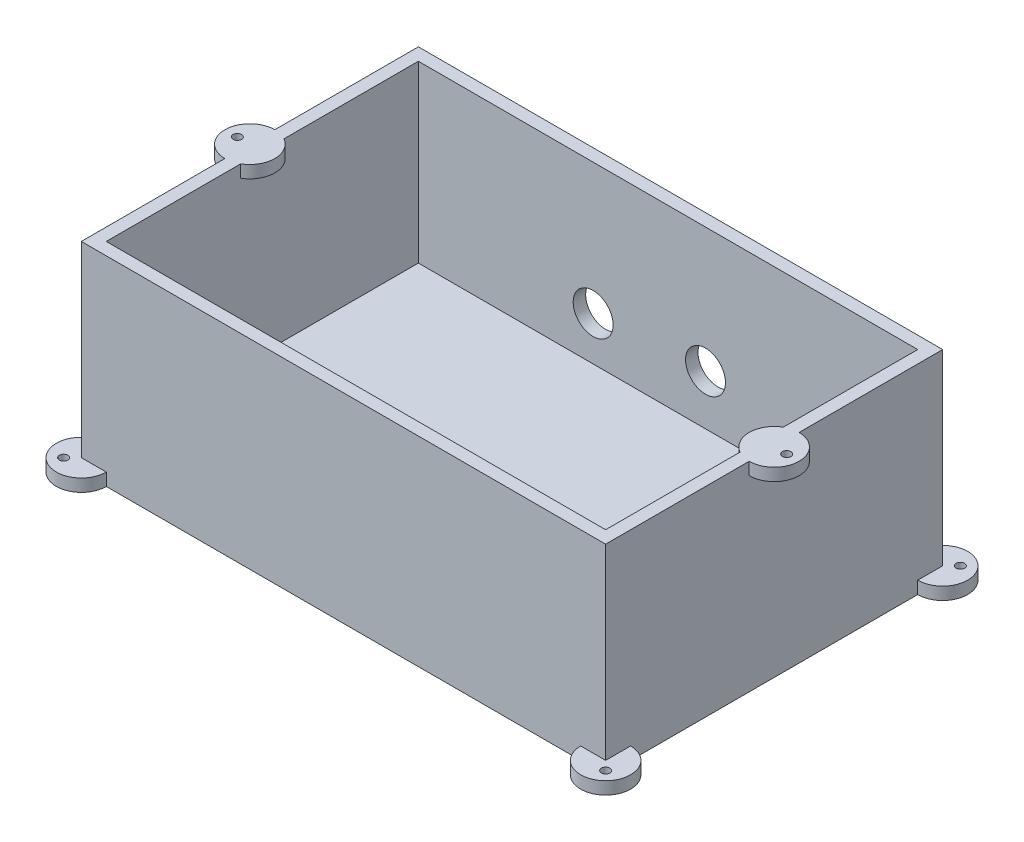
SolidWorks part; units mm, degrees
ref_plane "Front Plane" through (0, 0, 0) normal (0, 0, 1) x (1, 0, 0)
ref_plane "Top Plane" through (0, 0, 0) normal (0, 1, 0) x (1, 0, 0)
ref_plane "Right Plane" through (0, 0, 0) normal (1, 0, 0) x (0, 0, -1)
sketch "Sketch1" plane through (0, 0, 0) normal (0, 1, 0) x (1, 0, 0)
  line L0 (0, 0) -> (210, 0)
  line L1 (210, 0) -> (210, -135)
  line L2 (210, -135) -> (0, -135)
  line L3 (0, -135) -> (0, 0)
  line L4 (0, -135) -> (5, -135)
  line L5 (5, -135) -> (5, -5)
  line L6 (5, -5) -> (205, -5)
  line L7 (205, -5) -> (205, -130)
  line L8 (205, -130) -> (5, -130)
extrude "Boss-Extrude1" add sketch "Sketch1" along normal blind 70
sketch "Sketch2" plane through (0, 0, 0) normal (0, -1, 0) x (-1, 0, 0)
  line L0 (0, -135) -> (-210, -135)
  line L1 (-210, -135) -> (-210, 0)
  line L2 (-210, 0) -> (0, 0)
  line L3 (0, 0) -> (0, -135)
extrude "Boss-Extrude2" add sketch "Sketch2" along normal blind 10
sketch "Sketch3" plane through (0, -10, 0) normal (0, -1, 0) x (-1, 0, 0)
  circle A0 centre (-210, 0) radius 10
  circle A1 centre (0, 0) radius 10
  circle A2 centre (0, -135) radius 10
  circle A3 centre (-210, -135) radius 10
extrude "Boss-Extrude5" add sketch "Sketch3" against normal blind 5
sketch "Sketch7" plane through (0, -5, 0) normal (0, 1, 0) x (1, 0, 0)
  line L0 (0, 0) -> (-7.0711, 7.0711)
  line L1 (210, -135) -> (217.0711, -142.0711)
  line L2 (210, 0) -> (217.0711, 7.0711)
  line L3 (0, -135) -> (-7.0711, -142.0711)
  arc A0 (10, 0) -> (0, -10) centre (0, 0) ccw construction
  arc A1 (200, -135) -> (210, -125) centre (210, -135) ccw construction
  arc A2 (210, -10) -> (200, 0) centre (210, 0) ccw construction
  arc A3 (0, -125) -> (10, -135) centre (0, -135) ccw construction
  circle A4 centre (-3.5355, 3.5355) radius 1.7
  circle A5 centre (213.5355, 3.5355) radius 1.7
  circle A6 centre (213.5355, -138.5355) radius 1.7
  circle A7 centre (-3.5355, -138.5355) radius 1.7
extrude "Cut-Extrude2" cut sketch "Sketch7" against normal blind 5 contours L1 A6 | L1 A6 | L2 A5 | L2 A5 | L0 A4 | L0 A4 | L3 A7 | L3 A7
sketch "Sketch9" plane through (0, 0, 0) normal (0, 1, 0) x (1, 0, 0)
  line L0 (200, -135) -> (200, -125)
  line L1 (200, -125) -> (210, -125)
  line L2 (210, -125) -> (210, -10)
  line L3 (210, -10) -> (200, -10)
  line L4 (200, -10) -> (205, -15)
  line L5 (205, -5) -> (205, -130) construction
  line L6 (205, -15) -> (195, -5)
  line L7 (5, -5) -> (205, -5) construction
  line L8 (195, -5) -> (195, -130)
  line L9 (205, -130) -> (5, -130) construction
  line L10 (195, -130) -> (205, -120)
  line L11 (205, -120) -> (205, -15)
  line M2 (205, -130) -> (205, -5)
extrude "Cut-Extrude3" cut sketch "Sketch9" against normal blind 10 contours L8 L10 L4 L6 M2
sketch "Sketch10" plane through (0, 0, 0) normal (0, 1, 0) x (1, 0, 0)
  line L0 (195, -5) -> (195, -130)
  line L1 (195, -130) -> (185, -130)
  line L2 (195, -130) -> (5, -130) construction
  line L3 (185, -130) -> (185, -5)
  line L4 (5, -5) -> (205, -5) construction
  line L5 (185, -5) -> (195, -5)
extrude "Cut-Extrude4" cut sketch "Sketch10" against normal blind 10
sketch "Sketch11" plane through (0, 70, 0) normal (0, 1, 0) x (1, 0, 0)
  line L0 (210, 0) -> (210, -135) construction
  line L1 (210, -67.5) -> (220, -67.5)
  line L2 (0, -135) -> (0, 0) construction
  line L3 (0, -67.5) -> (-10, -67.5)
  circle A0 centre (210, -67.5) radius 10
  circle A1 centre (0, -67.5) radius 10
  circle A2 centre (-5, -67.5) radius 1.7
  circle A3 centre (215, -67.5) radius 1.7
  line M2 (5, -130) -> (5, -5)
  line M4 (205, -5) -> (205, -130)
  line M5 (0, 0) -> (0, -135)
  line M7 (210, -135) -> (210, 0)
extrude "Boss-Extrude6" add sketch "Sketch11" against normal blind 5 contours A3 L1 A0 M7 | A0 M4 | A0 M7 M4 | A3 L1 A0 M7 | A1 M2 | A1 M5 M2 | A2 L3 A1 M5 | A2 L3 A1 M5
sketch "Sketch12" plane through (0, 0, 0) normal (0, 0, -1) x (-1, 0, 0)
  line L0 (0, -10) -> (-75, -10)
  line L1 (-10, -10) -> (-200, -10) construction
  line L2 (-75, -10) -> (-75, 17.5)
  line L3 (0, -10) -> (-120, -10)
  line L4 (-120, -10) -> (-120, 20)
  circle A1 centre (-75, 17.5) radius 8
  circle A2 centre (-120, 20) radius 8
extrude "Cut-Extrude5" cut sketch "Sketch12" against normal blind 10
